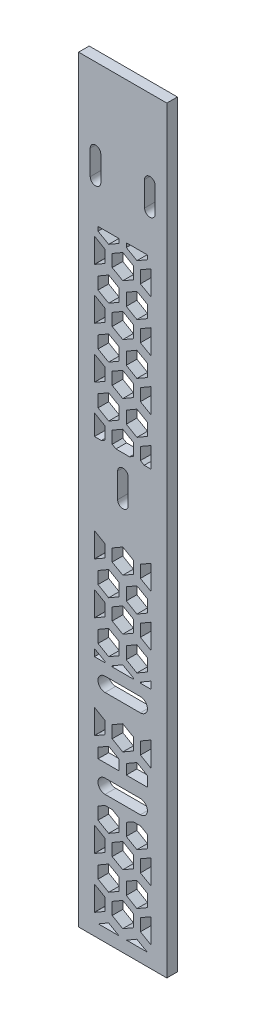
SolidWorks part; units mm, degrees
ref_plane "Front Plane" through (0, 0, 0) normal (0, 0, 1) x (1, 0, 0)
ref_plane "Top Plane" through (0, 0, 0) normal (0, 1, 0) x (1, 0, 0)
ref_plane "Right Plane" through (0, 0, 0) normal (1, 0, 0) x (0, 0, -1)
sketch "Sketch1" plane through (0, 0, 0) normal (0, 0, 1) x (1, 0, 0)
  line B0 (0, 114.5304) -> (25, 114.5304)
  line B1 (0, 114.5304) -> (0, -114.5304)
  line B2 (0, -114.5304) -> (25, -114.5304)
  line B3 (25, 114.5304) -> (25, -114.5304)
  line B4 (3.3, 89.1304) -> (0, 89.1304) construction
  line B5 (21.7, 89.1304) -> (25, 89.1304) construction
  line B6 (0, -100.1081) -> (25, -100.1081) construction
  circle B7 centre (4.8, 89.1304) radius 1.5
  circle B8 centre (20.2, 89.1304) radius 1.5
  circle B9 centre (12.5588, 13.7722) radius 1.5
  spline B10 degree 3 poles (11.075, -109.3281) (11.075, -112.3281) (14.075, -112.3281) (14.075, -109.3281) (14.075, -106.3281) (11.075, -106.3281) (11.075, -109.3281) (11.075, -112.3281) (14.075, -112.3281) knots -0.5 0 0 0 0.5 0.5 0.5 1 1 1 1.5 1.5 1.5 weights 1 0.333333 0.333333 1 0.333333 0.333333 1 0.333333 0.333333 only from (11.075, -109.3281) to (11.075, -109.3281)
sketch_block_instance "Block-sideExtraSupport-1"
sketch_block "Block-sideExtraSupport" parameters "D1"=25
extrude "Boss-Extrude1" add sketch "Sketch1" along normal blind 3 contours B1 B6 B3 B0 B9 B8 B7
sketch "Sketch2" plane through (0, 0, 3) normal (0, 0, 1) x (1, 0, 0)
  line L1 (0, -114.5304) -> (25, -114.5304) construction
  point P3 (12.5, -114.5304)
  line B0 (0, -24.3132) -> (40.525, -24.3132) construction
  line B1 (0, -24.3132) -> (0, -74.3132) construction
  line B2 (0, -74.3132) -> (40.525, -74.3132) construction
  line B3 (40.525, -24.3132) -> (40.525, -74.3132) construction
  line B4 (32.525, -24.3132) -> (28.125, -24.3132) construction
  line B5 (20.2625, -24.3132) -> (20.2625, -49.3132) construction
  line B6 (20.2625, -49.3132) -> (0, -49.3132) construction
  line B7 (20.2625, -36.8132) -> (0, -36.8132) construction
  line B8 (28.125, -64.3132) -> (32.525, -64.3132) construction
  line B9 (32.525, -64.3132) -> (32.525, -34.3132) construction
  line B10 (28.125, -64.3132) -> (28.125, -34.3132) construction
  line B11 (28.125, -34.3132) -> (32.525, -34.3132) construction
  line B12 (27.625, -64.8132) -> (33.025, -64.8132) construction
  line B13 (33.025, -64.8132) -> (33.025, -33.8132) construction
  line B14 (27.625, -33.8132) -> (33.025, -33.8132) construction
  line B15 (27.625, -64.8132) -> (27.625, -33.8132) construction
  line B16 (0, -100.1081) -> (25, -100.1081) construction
  line B17 (25, -114.5304) -> (0, -114.5304) construction
  line B18 (12.5, -100.1081) -> (12.5, -61.8132) construction
  line B19 (12.5, -114.5304) -> (12.5, -100.1081) construction
  line B20 (7.5, -36.8132) -> (17.5, -36.8132)
  line B21 (7.5, -34.8132) -> (17.5, -34.8132)
  line B22 (7.5, -38.8132) -> (17.5, -38.8132)
  line B23 (7.5, -61.8132) -> (17.5, -61.8132)
  line B24 (7.5, -63.8132) -> (17.5, -63.8132)
  line B25 (7.5, -59.8132) -> (17.5, -59.8132)
  arc B26 (7.5, -34.8132) -> (7.5, -38.8132) centre (7.5, -36.8132) ccw
  arc B27 (17.5, -38.8132) -> (17.5, -34.8132) centre (17.5, -36.8132) ccw
  arc B28 (7.5, -63.8132) -> (7.5, -59.8132) centre (7.5, -61.8132) cw
  arc B29 (17.5, -59.8132) -> (17.5, -63.8132) centre (17.5, -61.8132) cw
sketch_block_instance "Block-SidePanelSketch2-1"
sketch_block "Block-SidePanelSketch2" parameters "D1"=50, "D2"=4, "D3"=10, "D4"=8
extrude "Cut-Extrude1" cut sketch "Sketch2" against normal through all
sketch "Sketch3" plane through (0, 0, 3) normal (0, 0, 1) x (1, 0, 0)
  line L0 (12.5, 114.5304) -> (12.5, -114.5304) construction
  line L1 (0, 114.5304) -> (25, 114.5304) construction
  line L2 (0, -114.5304) -> (25, -114.5304) construction
  line L3 (4.8, 92.6304) -> (4.8, 85.6304) construction
  line L4 (6.3, 92.6304) -> (6.3, 85.6304)
  line L5 (3.3, 92.6304) -> (3.3, 85.6304)
  line L6 (20.2, 92.6304) -> (20.2, 85.6304) construction
  line L7 (18.7, 92.6304) -> (18.7, 85.6304)
  line L8 (21.7, 92.6304) -> (21.7, 85.6304)
  line L9 (12.5588, 17.2722) -> (12.5588, 10.2722) construction
  line L10 (14.0588, 17.2722) -> (14.0588, 10.2722)
  line L11 (11.0588, 17.2722) -> (11.0588, 10.2722)
  arc A1 (6.3, 92.6304) -> (3.3, 92.6304) centre (4.8, 92.6304) ccw
  arc A2 (3.3, 85.6304) -> (6.3, 85.6304) centre (4.8, 85.6304) ccw
  circle A3 centre (4.8, 89.1304) radius 1.5 construction
  arc A4 (18.7, 92.6304) -> (21.7, 92.6304) centre (20.2, 92.6304) cw
  arc A5 (21.7, 85.6304) -> (18.7, 85.6304) centre (20.2, 85.6304) cw
  arc A6 (14.0588, 17.2722) -> (11.0588, 17.2722) centre (12.5588, 17.2722) ccw
  arc A7 (11.0588, 10.2722) -> (14.0588, 10.2722) centre (12.5588, 10.2722) ccw
  circle A8 centre (12.5588, 13.7722) radius 1.5 construction
  point P6 (4.8, 89.1304)
  point P10 (12.5588, 18.7722)
  point P14 (12.5588, 13.7722)
  point P19 (4.8, 94.1304)
  point P22 (20.2, 89.1304)
  dimension "D1" = 5
  dimension "D2" = 5
extrude "Cut-Extrude2" cut sketch "Sketch3" against normal through all
sketch "Sketch4" plane through (0, 0, 3) normal (0, 0, 1) x (1, 0, 0)
  line L0 (25, 114.5304) -> (25, -114.5304) construction
  line L1 (4.5, -66.5304) -> (20.5, -66.5304)
  line L2 (4.5, -66.5304) -> (4.5, -96.5304)
  line L3 (4.5, -96.5304) -> (20.5, -96.5304)
  line L4 (20.5, -66.5304) -> (20.5, -96.5304)
  line L5 (4.5, -66.5304) -> (20.5, -96.5304) construction
  line L6 (4.5, -96.5304) -> (20.5, -66.5304) construction
  line L7 (4.5, -43.0716) -> (20.5, -43.0716)
  line L8 (4.5, -43.0716) -> (4.5, -56.0716)
  line L9 (4.5, -56.0716) -> (20.5, -56.0716)
  line L10 (20.5, -43.0716) -> (20.5, -56.0716)
  line L11 (4.5, -43.0716) -> (20.5, -56.0716) construction
  line L12 (4.5, -56.0716) -> (20.5, -43.0716) construction
  line L13 (4.5, 22.4696) -> (20.5, 22.4696)
  line L14 (4.5, 22.4696) -> (4.5, 74.5304)
  line L15 (4.5, 74.5304) -> (20.5, 74.5304)
  line L16 (20.5, 22.4696) -> (20.5, 74.5304)
  line L17 (4.5, 22.4696) -> (20.5, 74.5304) construction
  line L18 (4.5, 74.5304) -> (20.5, 22.4696) construction
  line L19 (4.5, -31.5304) -> (20.5, -31.5304)
  line L20 (4.5, -31.5304) -> (4.5, 5.4696)
  line L21 (4.5, 5.4696) -> (20.5, 5.4696)
  line L22 (20.5, -31.5304) -> (20.5, 5.4696)
  line L23 (4.5, -31.5304) -> (20.5, 5.4696) construction
  line L24 (4.5, 5.4696) -> (20.5, -31.5304) construction
  line L25 (0, 114.5304) -> (0, -114.5304) construction
  line L26 (0, -114.5304) -> (25, -114.5304) construction
  line L27 (0, 114.5304) -> (25, 114.5304) construction
  line L28 (11.5204, -100.036) -> (11.5204, -96.5719)
  line L29 (3.5204, -100.036) -> (3.5204, -96.5719)
  line L30 (3.5204, -96.5719) -> (0.5204, -94.8398)
  line L31 (0.5204, -94.8398) -> (-2.4796, -96.5719)
  line L32 (-2.4796, -96.5719) -> (-2.4796, -100.036)
  line L33 (-2.4796, -100.036) -> (0.5204, -101.7681)
  line L34 (0.5204, -101.7681) -> (3.5204, -100.036)
  line L35 (7.5204, -106.9642) -> (7.5204, -103.5001)
  line L36 (7.5204, -103.5001) -> (4.5204, -101.7681)
  line L37 (4.5204, -101.7681) -> (1.5204, -103.5001)
  line L38 (1.5204, -103.5001) -> (1.5204, -106.9642)
  line L39 (1.5204, -106.9642) -> (4.5204, -108.6963)
  line L40 (4.5204, -108.6963) -> (7.5204, -106.9642)
  line L41 (11.5204, -96.5719) -> (8.5204, -94.8398)
  line L42 (8.5204, -94.8398) -> (5.5204, -96.5719)
  line L43 (5.5204, -96.5719) -> (5.5204, -100.036)
  line L44 (5.5204, -100.036) -> (8.5204, -101.7681)
  line L45 (8.5204, -101.7681) -> (11.5204, -100.036)
  line L46 (15.5204, -106.9642) -> (15.5204, -103.5001)
  line L47 (15.5204, -103.5001) -> (12.5204, -101.7681)
  line L48 (12.5204, -101.7681) -> (9.5204, -103.5001)
  line L49 (9.5204, -103.5001) -> (9.5204, -106.9642)
  line L50 (9.5204, -106.9642) -> (12.5204, -108.6963)
  line L51 (12.5204, -108.6963) -> (15.5204, -106.9642)
  line L52 (19.5204, -100.036) -> (19.5204, -96.5719)
  line L53 (19.5204, -96.5719) -> (16.5204, -94.8398)
  line L54 (16.5204, -94.8398) -> (13.5204, -96.5719)
  line L55 (13.5204, -96.5719) -> (13.5204, -100.036)
  line L56 (13.5204, -100.036) -> (16.5204, -101.7681)
  line L57 (16.5204, -101.7681) -> (19.5204, -100.036)
  line L58 (23.5204, -106.9642) -> (23.5204, -103.5001)
  line L59 (23.5204, -103.5001) -> (20.5204, -101.7681)
  line L60 (20.5204, -101.7681) -> (17.5204, -103.5001)
  line L61 (17.5204, -103.5001) -> (17.5204, -106.9642)
  line L62 (17.5204, -106.9642) -> (20.5204, -108.6963)
  line L63 (20.5204, -108.6963) -> (23.5204, -106.9642)
  line L64 (11.5204, -85.586) -> (11.5204, -82.1219)
  line L65 (11.5204, -82.1219) -> (8.5204, -80.3898)
  line L66 (8.5204, -80.3898) -> (5.5204, -82.1219)
  line L67 (5.5204, -82.1219) -> (5.5204, -85.586)
  line L68 (5.5204, -85.586) -> (8.5204, -87.3181)
  line L69 (8.5204, -87.3181) -> (11.5204, -85.586)
  line L70 (15.5204, -92.5142) -> (15.5204, -89.0501)
  line L71 (15.5204, -89.0501) -> (12.5204, -87.3181)
  line L72 (12.5204, -87.3181) -> (9.5204, -89.0501)
  line L73 (9.5204, -89.0501) -> (9.5204, -92.5142)
  line L74 (9.5204, -92.5142) -> (12.5204, -94.2463)
  line L75 (12.5204, -94.2463) -> (15.5204, -92.5142)
  line L76 (19.5204, -85.586) -> (19.5204, -82.1219)
  line L77 (19.5204, -82.1219) -> (16.5204, -80.3898)
  line L78 (16.5204, -80.3898) -> (13.5204, -82.1219)
  line L79 (13.5204, -82.1219) -> (13.5204, -85.586)
  line L80 (13.5204, -85.586) -> (16.5204, -87.3181)
  line L81 (16.5204, -87.3181) -> (19.5204, -85.586)
  line L82 (23.5204, -92.5142) -> (23.5204, -89.0501)
  line L83 (23.5204, -89.0501) -> (20.5204, -87.3181)
  line L84 (20.5204, -87.3181) -> (17.5204, -89.0501)
  line L85 (17.5204, -89.0501) -> (17.5204, -92.5142)
  line L86 (17.5204, -92.5142) -> (20.5204, -94.2463)
  line L87 (20.5204, -94.2463) -> (23.5204, -92.5142)
  line L88 (11.5204, -71.136) -> (11.5204, -67.6719)
  line L89 (11.5204, -67.6719) -> (8.5204, -65.9398)
  line L90 (8.5204, -65.9398) -> (5.5204, -67.6719)
  line L91 (5.5204, -67.6719) -> (5.5204, -71.136)
  line L92 (5.5204, -71.136) -> (8.5204, -72.8681)
  line L93 (8.5204, -72.8681) -> (11.5204, -71.136)
  line L94 (15.5204, -78.0642) -> (15.5204, -74.6001)
  line L95 (15.5204, -74.6001) -> (12.5204, -72.8681)
  line L96 (12.5204, -72.8681) -> (9.5204, -74.6001)
  line L97 (9.5204, -74.6001) -> (9.5204, -78.0642)
  line L98 (9.5204, -78.0642) -> (12.5204, -79.7963)
  line L99 (12.5204, -79.7963) -> (15.5204, -78.0642)
  line L100 (19.5204, -71.136) -> (19.5204, -67.6719)
  line L101 (19.5204, -67.6719) -> (16.5204, -65.9398)
  line L102 (16.5204, -65.9398) -> (13.5204, -67.6719)
  line L103 (13.5204, -67.6719) -> (13.5204, -71.136)
  line L104 (13.5204, -71.136) -> (16.5204, -72.8681)
  line L105 (16.5204, -72.8681) -> (19.5204, -71.136)
  line L106 (23.5204, -78.0642) -> (23.5204, -74.6001)
  line L107 (23.5204, -74.6001) -> (20.5204, -72.8681)
  line L108 (20.5204, -72.8681) -> (17.5204, -74.6001)
  line L109 (17.5204, -74.6001) -> (17.5204, -78.0642)
  line L110 (17.5204, -78.0642) -> (20.5204, -79.7963)
  line L111 (20.5204, -79.7963) -> (23.5204, -78.0642)
  line L112 (11.5204, -56.686) -> (11.5204, -53.2219)
  line L113 (11.5204, -53.2219) -> (8.5204, -51.4898)
  line L114 (8.5204, -51.4898) -> (5.5204, -53.2219)
  line L115 (5.5204, -53.2219) -> (5.5204, -56.686)
  line L116 (5.5204, -56.686) -> (8.5204, -58.4181)
  line L117 (8.5204, -58.4181) -> (11.5204, -56.686)
  line L118 (15.5204, -63.6142) -> (15.5204, -60.1501)
  line L119 (15.5204, -60.1501) -> (12.5204, -58.4181)
  line L120 (12.5204, -58.4181) -> (9.5204, -60.1501)
  line L121 (9.5204, -60.1501) -> (9.5204, -63.6142)
  line L122 (9.5204, -63.6142) -> (12.5204, -65.3463)
  line L123 (12.5204, -65.3463) -> (15.5204, -63.6142)
  line L124 (19.5204, -56.686) -> (19.5204, -53.2219)
  line L125 (19.5204, -53.2219) -> (16.5204, -51.4898)
  line L126 (16.5204, -51.4898) -> (13.5204, -53.2219)
  line L127 (13.5204, -53.2219) -> (13.5204, -56.686)
  line L128 (13.5204, -56.686) -> (16.5204, -58.4181)
  line L129 (16.5204, -58.4181) -> (19.5204, -56.686)
  line L130 (23.5204, -63.6142) -> (23.5204, -60.1501)
  line L131 (23.5204, -60.1501) -> (20.5204, -58.4181)
  line L132 (20.5204, -58.4181) -> (17.5204, -60.1501)
  line L133 (17.5204, -60.1501) -> (17.5204, -63.6142)
  line L134 (17.5204, -63.6142) -> (20.5204, -65.3463)
  line L135 (20.5204, -65.3463) -> (23.5204, -63.6142)
  line L136 (11.5204, -42.236) -> (11.5204, -38.7719)
  line L137 (11.5204, -38.7719) -> (8.5204, -37.0398)
  line L138 (8.5204, -37.0398) -> (5.5204, -38.7719)
  line L139 (5.5204, -38.7719) -> (5.5204, -42.236)
  line L140 (5.5204, -42.236) -> (8.5204, -43.9681)
  line L141 (8.5204, -43.9681) -> (11.5204, -42.236)
  line L142 (15.5204, -49.1642) -> (15.5204, -45.7001)
  line L143 (15.5204, -45.7001) -> (12.5204, -43.9681)
  line L144 (12.5204, -43.9681) -> (9.5204, -45.7001)
  line L145 (9.5204, -45.7001) -> (9.5204, -49.1642)
  line L146 (9.5204, -49.1642) -> (12.5204, -50.8963)
  line L147 (12.5204, -50.8963) -> (15.5204, -49.1642)
  line L148 (19.5204, -42.236) -> (19.5204, -38.7719)
  line L149 (19.5204, -38.7719) -> (16.5204, -37.0398)
  line L150 (16.5204, -37.0398) -> (13.5204, -38.7719)
  line L151 (13.5204, -38.7719) -> (13.5204, -42.236)
  line L152 (13.5204, -42.236) -> (16.5204, -43.9681)
  line L153 (16.5204, -43.9681) -> (19.5204, -42.236)
  line L154 (23.5204, -49.1642) -> (23.5204, -45.7001)
  line L155 (23.5204, -45.7001) -> (20.5204, -43.9681)
  line L156 (20.5204, -43.9681) -> (17.5204, -45.7001)
  line L157 (17.5204, -45.7001) -> (17.5204, -49.1642)
  line L158 (17.5204, -49.1642) -> (20.5204, -50.8963)
  line L159 (20.5204, -50.8963) -> (23.5204, -49.1642)
  line L160 (11.5204, -27.786) -> (11.5204, -24.3219)
  line L161 (11.5204, -24.3219) -> (8.5204, -22.5898)
  line L162 (8.5204, -22.5898) -> (5.5204, -24.3219)
  line L163 (5.5204, -24.3219) -> (5.5204, -27.786)
  line L164 (5.5204, -27.786) -> (8.5204, -29.5181)
  line L165 (8.5204, -29.5181) -> (11.5204, -27.786)
  line L166 (15.5204, -34.7142) -> (15.5204, -31.2501)
  line L167 (15.5204, -31.2501) -> (12.5204, -29.5181)
  line L168 (12.5204, -29.5181) -> (9.5204, -31.2501)
  line L169 (9.5204, -31.2501) -> (9.5204, -34.7142)
  line L170 (9.5204, -34.7142) -> (12.5204, -36.4463)
  line L171 (12.5204, -36.4463) -> (15.5204, -34.7142)
  line L172 (19.5204, -27.786) -> (19.5204, -24.3219)
  line L173 (19.5204, -24.3219) -> (16.5204, -22.5898)
  line L174 (16.5204, -22.5898) -> (13.5204, -24.3219)
  line L175 (13.5204, -24.3219) -> (13.5204, -27.786)
  line L176 (13.5204, -27.786) -> (16.5204, -29.5181)
  line L177 (16.5204, -29.5181) -> (19.5204, -27.786)
  line L178 (23.5204, -34.7142) -> (23.5204, -31.2501)
  line L179 (23.5204, -31.2501) -> (20.5204, -29.5181)
  line L180 (20.5204, -29.5181) -> (17.5204, -31.2501)
  line L181 (17.5204, -31.2501) -> (17.5204, -34.7142)
  line L182 (17.5204, -34.7142) -> (20.5204, -36.4463)
  line L183 (20.5204, -36.4463) -> (23.5204, -34.7142)
  line L184 (11.5204, -13.336) -> (11.5204, -9.8719)
  line L185 (11.5204, -9.8719) -> (8.5204, -8.1398)
  line L186 (8.5204, -8.1398) -> (5.5204, -9.8719)
  line L187 (5.5204, -9.8719) -> (5.5204, -13.336)
  line L188 (5.5204, -13.336) -> (8.5204, -15.0681)
  line L189 (8.5204, -15.0681) -> (11.5204, -13.336)
  line L190 (15.5204, -20.2642) -> (15.5204, -16.8001)
  line L191 (15.5204, -16.8001) -> (12.5204, -15.0681)
  line L192 (12.5204, -15.0681) -> (9.5204, -16.8001)
  line L193 (9.5204, -16.8001) -> (9.5204, -20.2642)
  line L194 (9.5204, -20.2642) -> (12.5204, -21.9963)
  line L195 (12.5204, -21.9963) -> (15.5204, -20.2642)
  line L196 (19.5204, -13.336) -> (19.5204, -9.8719)
  line L197 (19.5204, -9.8719) -> (16.5204, -8.1398)
  line L198 (16.5204, -8.1398) -> (13.5204, -9.8719)
  line L199 (13.5204, -9.8719) -> (13.5204, -13.336)
  line L200 (13.5204, -13.336) -> (16.5204, -15.0681)
  line L201 (16.5204, -15.0681) -> (19.5204, -13.336)
  line L202 (23.5204, -20.2642) -> (23.5204, -16.8001)
  line L203 (23.5204, -16.8001) -> (20.5204, -15.0681)
  line L204 (20.5204, -15.0681) -> (17.5204, -16.8001)
  line L205 (17.5204, -16.8001) -> (17.5204, -20.2642)
  line L206 (17.5204, -20.2642) -> (20.5204, -21.9963)
  line L207 (20.5204, -21.9963) -> (23.5204, -20.2642)
  line L208 (11.5204, 1.114) -> (11.5204, 4.5781)
  line L209 (11.5204, 4.5781) -> (8.5204, 6.3102)
  line L210 (8.5204, 6.3102) -> (5.5204, 4.5781)
  line L211 (5.5204, 4.5781) -> (5.5204, 1.114)
  line L212 (5.5204, 1.114) -> (8.5204, -0.6181)
  line L213 (8.5204, -0.6181) -> (11.5204, 1.114)
  line L214 (15.5204, -5.8142) -> (15.5204, -2.3501)
  line L215 (15.5204, -2.3501) -> (12.5204, -0.6181)
  line L216 (12.5204, -0.6181) -> (9.5204, -2.3501)
  line L217 (9.5204, -2.3501) -> (9.5204, -5.8142)
  line L218 (9.5204, -5.8142) -> (12.5204, -7.5463)
  line L219 (12.5204, -7.5463) -> (15.5204, -5.8142)
  line L220 (19.5204, 1.114) -> (19.5204, 4.5781)
  line L221 (19.5204, 4.5781) -> (16.5204, 6.3102)
  line L222 (16.5204, 6.3102) -> (13.5204, 4.5781)
  line L223 (13.5204, 4.5781) -> (13.5204, 1.114)
  line L224 (13.5204, 1.114) -> (16.5204, -0.6181)
  line L225 (16.5204, -0.6181) -> (19.5204, 1.114)
  line L226 (23.5204, -5.8142) -> (23.5204, -2.3501)
  line L227 (23.5204, -2.3501) -> (20.5204, -0.6181)
  line L228 (20.5204, -0.6181) -> (17.5204, -2.3501)
  line L229 (17.5204, -2.3501) -> (17.5204, -5.8142)
  line L230 (17.5204, -5.8142) -> (20.5204, -7.5463)
  line L231 (20.5204, -7.5463) -> (23.5204, -5.8142)
  line L232 (11.5204, 15.564) -> (11.5204, 19.0281)
  line L233 (11.5204, 19.0281) -> (8.5204, 20.7602)
  line L234 (8.5204, 20.7602) -> (5.5204, 19.0281)
  line L235 (5.5204, 19.0281) -> (5.5204, 15.564)
  line L236 (5.5204, 15.564) -> (8.5204, 13.8319)
  line L237 (8.5204, 13.8319) -> (11.5204, 15.564)
  line L238 (15.5204, 8.6358) -> (15.5204, 12.0999)
  line L239 (15.5204, 12.0999) -> (12.5204, 13.8319)
  line L240 (12.5204, 13.8319) -> (9.5204, 12.0999)
  line L241 (9.5204, 12.0999) -> (9.5204, 8.6358)
  line L242 (9.5204, 8.6358) -> (12.5204, 6.9037)
  line L243 (12.5204, 6.9037) -> (15.5204, 8.6358)
  line L244 (19.5204, 15.564) -> (19.5204, 19.0281)
  line L245 (19.5204, 19.0281) -> (16.5204, 20.7602)
  line L246 (16.5204, 20.7602) -> (13.5204, 19.0281)
  line L247 (13.5204, 19.0281) -> (13.5204, 15.564)
  line L248 (13.5204, 15.564) -> (16.5204, 13.8319)
  line L249 (16.5204, 13.8319) -> (19.5204, 15.564)
  line L250 (23.5204, 8.6358) -> (23.5204, 12.0999)
  line L251 (23.5204, 12.0999) -> (20.5204, 13.8319)
  line L252 (20.5204, 13.8319) -> (17.5204, 12.0999)
  line L253 (17.5204, 12.0999) -> (17.5204, 8.6358)
  line L254 (17.5204, 8.6358) -> (20.5204, 6.9037)
  line L255 (20.5204, 6.9037) -> (23.5204, 8.6358)
  line L256 (11.5204, 30.014) -> (11.5204, 33.4781)
  line L257 (11.5204, 33.4781) -> (8.5204, 35.2102)
  line L258 (8.5204, 35.2102) -> (5.5204, 33.4781)
  line L259 (5.5204, 33.4781) -> (5.5204, 30.014)
  line L260 (5.5204, 30.014) -> (8.5204, 28.2819)
  line L261 (8.5204, 28.2819) -> (11.5204, 30.014)
  line L262 (15.5204, 23.0858) -> (15.5204, 26.5499)
  line L263 (15.5204, 26.5499) -> (12.5204, 28.2819)
  line L264 (12.5204, 28.2819) -> (9.5204, 26.5499)
  line L265 (9.5204, 26.5499) -> (9.5204, 23.0858)
  line L266 (9.5204, 23.0858) -> (12.5204, 21.3537)
  line L267 (12.5204, 21.3537) -> (15.5204, 23.0858)
  line L268 (19.5204, 30.014) -> (19.5204, 33.4781)
  line L269 (19.5204, 33.4781) -> (16.5204, 35.2102)
  line L270 (16.5204, 35.2102) -> (13.5204, 33.4781)
  line L271 (13.5204, 33.4781) -> (13.5204, 30.014)
  line L272 (13.5204, 30.014) -> (16.5204, 28.2819)
  line L273 (16.5204, 28.2819) -> (19.5204, 30.014)
  line L274 (23.5204, 23.0858) -> (23.5204, 26.5499)
  line L275 (23.5204, 26.5499) -> (20.5204, 28.2819)
  line L276 (20.5204, 28.2819) -> (17.5204, 26.5499)
  line L277 (17.5204, 26.5499) -> (17.5204, 23.0858)
  line L278 (17.5204, 23.0858) -> (20.5204, 21.3537)
  line L279 (20.5204, 21.3537) -> (23.5204, 23.0858)
  line L280 (11.5204, 44.464) -> (11.5204, 47.9281)
  line L281 (11.5204, 47.9281) -> (8.5204, 49.6602)
  line L282 (8.5204, 49.6602) -> (5.5204, 47.9281)
  line L283 (5.5204, 47.9281) -> (5.5204, 44.464)
  line L284 (5.5204, 44.464) -> (8.5204, 42.7319)
  line L285 (8.5204, 42.7319) -> (11.5204, 44.464)
  line L286 (15.5204, 37.5358) -> (15.5204, 40.9999)
  line L287 (15.5204, 40.9999) -> (12.5204, 42.7319)
  line L288 (12.5204, 42.7319) -> (9.5204, 40.9999)
  line L289 (9.5204, 40.9999) -> (9.5204, 37.5358)
  line L290 (9.5204, 37.5358) -> (12.5204, 35.8037)
  line L291 (12.5204, 35.8037) -> (15.5204, 37.5358)
  line L292 (19.5204, 44.464) -> (19.5204, 47.9281)
  line L293 (19.5204, 47.9281) -> (16.5204, 49.6602)
  line L294 (16.5204, 49.6602) -> (13.5204, 47.9281)
  line L295 (13.5204, 47.9281) -> (13.5204, 44.464)
  line L296 (13.5204, 44.464) -> (16.5204, 42.7319)
  line L297 (16.5204, 42.7319) -> (19.5204, 44.464)
  line L298 (23.5204, 37.5358) -> (23.5204, 40.9999)
  line L299 (23.5204, 40.9999) -> (20.5204, 42.7319)
  line L300 (20.5204, 42.7319) -> (17.5204, 40.9999)
  line L301 (17.5204, 40.9999) -> (17.5204, 37.5358)
  line L302 (17.5204, 37.5358) -> (20.5204, 35.8037)
  line L303 (20.5204, 35.8037) -> (23.5204, 37.5358)
  line L304 (11.5204, 58.914) -> (11.5204, 62.3781)
  line L305 (11.5204, 62.3781) -> (8.5204, 64.1102)
  line L306 (8.5204, 64.1102) -> (5.5204, 62.3781)
  line L307 (5.5204, 62.3781) -> (5.5204, 58.914)
  line L308 (5.5204, 58.914) -> (8.5204, 57.1819)
  line L309 (8.5204, 57.1819) -> (11.5204, 58.914)
  line L310 (15.5204, 51.9858) -> (15.5204, 55.4499)
  line L311 (15.5204, 55.4499) -> (12.5204, 57.1819)
  line L312 (12.5204, 57.1819) -> (9.5204, 55.4499)
  line L313 (9.5204, 55.4499) -> (9.5204, 51.9858)
  line L314 (9.5204, 51.9858) -> (12.5204, 50.2537)
  line L315 (12.5204, 50.2537) -> (15.5204, 51.9858)
  line L316 (19.5204, 58.914) -> (19.5204, 62.3781)
  line L317 (19.5204, 62.3781) -> (16.5204, 64.1102)
  line L318 (16.5204, 64.1102) -> (13.5204, 62.3781)
  line L319 (13.5204, 62.3781) -> (13.5204, 58.914)
  line L320 (13.5204, 58.914) -> (16.5204, 57.1819)
  line L321 (16.5204, 57.1819) -> (19.5204, 58.914)
  line L322 (23.5204, 51.9858) -> (23.5204, 55.4499)
  line L323 (23.5204, 55.4499) -> (20.5204, 57.1819)
  line L324 (20.5204, 57.1819) -> (17.5204, 55.4499)
  line L325 (17.5204, 55.4499) -> (17.5204, 51.9858)
  line L326 (17.5204, 51.9858) -> (20.5204, 50.2537)
  line L327 (20.5204, 50.2537) -> (23.5204, 51.9858)
  line L328 (11.5204, 73.364) -> (11.5204, 76.8281)
  line L329 (11.5204, 76.8281) -> (8.5204, 78.5602)
  line L330 (8.5204, 78.5602) -> (5.5204, 76.8281)
  line L331 (5.5204, 76.8281) -> (5.5204, 73.364)
  line L332 (5.5204, 73.364) -> (8.5204, 71.6319)
  line L333 (8.5204, 71.6319) -> (11.5204, 73.364)
  line L334 (15.5204, 66.4358) -> (15.5204, 69.8999)
  line L335 (15.5204, 69.8999) -> (12.5204, 71.6319)
  line L336 (12.5204, 71.6319) -> (9.5204, 69.8999)
  line L337 (9.5204, 69.8999) -> (9.5204, 66.4358)
  line L338 (9.5204, 66.4358) -> (12.5204, 64.7037)
  line L339 (12.5204, 64.7037) -> (15.5204, 66.4358)
  line L340 (19.5204, 73.364) -> (19.5204, 76.8281)
  line L341 (19.5204, 76.8281) -> (16.5204, 78.5602)
  line L342 (16.5204, 78.5602) -> (13.5204, 76.8281)
  line L343 (13.5204, 76.8281) -> (13.5204, 73.364)
  line L344 (13.5204, 73.364) -> (16.5204, 71.6319)
  line L345 (16.5204, 71.6319) -> (19.5204, 73.364)
  line L346 (23.5204, 66.4358) -> (23.5204, 69.8999)
  line L347 (23.5204, 69.8999) -> (20.5204, 71.6319)
  line L348 (20.5204, 71.6319) -> (17.5204, 69.8999)
  line L349 (17.5204, 69.8999) -> (17.5204, 66.4358)
  line L350 (17.5204, 66.4358) -> (20.5204, 64.7037)
  line L351 (20.5204, 64.7037) -> (23.5204, 66.4358)
  line L352 (3.5204, -85.586) -> (3.5204, -82.1219)
  line L353 (3.5204, -82.1219) -> (0.5204, -80.3898)
  line L354 (0.5204, -80.3898) -> (-2.4796, -82.1219)
  line L355 (-2.4796, -82.1219) -> (-2.4796, -85.586)
  line L356 (-2.4796, -85.586) -> (0.5204, -87.3181)
  line L357 (0.5204, -87.3181) -> (3.5204, -85.586)
  line L358 (7.5204, -92.5142) -> (7.5204, -89.0501)
  line L359 (7.5204, -89.0501) -> (4.5204, -87.3181)
  line L360 (4.5204, -87.3181) -> (1.5204, -89.0501)
  line L361 (1.5204, -89.0501) -> (1.5204, -92.5142)
  line L362 (1.5204, -92.5142) -> (4.5204, -94.2463)
  line L363 (4.5204, -94.2463) -> (7.5204, -92.5142)
  line L364 (3.5204, -71.136) -> (3.5204, -67.6719)
  line L365 (3.5204, -67.6719) -> (0.5204, -65.9398)
  line L366 (0.5204, -65.9398) -> (-2.4796, -67.6719)
  line L367 (-2.4796, -67.6719) -> (-2.4796, -71.136)
  line L368 (-2.4796, -71.136) -> (0.5204, -72.8681)
  line L369 (0.5204, -72.8681) -> (3.5204, -71.136)
  line L370 (7.5204, -78.0642) -> (7.5204, -74.6001)
  line L371 (7.5204, -74.6001) -> (4.5204, -72.8681)
  line L372 (4.5204, -72.8681) -> (1.5204, -74.6001)
  line L373 (1.5204, -74.6001) -> (1.5204, -78.0642)
  line L374 (1.5204, -78.0642) -> (4.5204, -79.7963)
  line L375 (4.5204, -79.7963) -> (7.5204, -78.0642)
  line L376 (3.5204, -56.686) -> (3.5204, -53.2219)
  line L377 (3.5204, -53.2219) -> (0.5204, -51.4898)
  line L378 (0.5204, -51.4898) -> (-2.4796, -53.2219)
  line L379 (-2.4796, -53.2219) -> (-2.4796, -56.686)
  line L380 (-2.4796, -56.686) -> (0.5204, -58.4181)
  line L381 (0.5204, -58.4181) -> (3.5204, -56.686)
  line L382 (7.5204, -63.6142) -> (7.5204, -60.1501)
  line L383 (7.5204, -60.1501) -> (4.5204, -58.4181)
  line L384 (4.5204, -58.4181) -> (1.5204, -60.1501)
  line L385 (1.5204, -60.1501) -> (1.5204, -63.6142)
  line L386 (1.5204, -63.6142) -> (4.5204, -65.3463)
  line L387 (4.5204, -65.3463) -> (7.5204, -63.6142)
  line L388 (3.5204, -42.236) -> (3.5204, -38.7719)
  line L389 (3.5204, -38.7719) -> (0.5204, -37.0398)
  line L390 (0.5204, -37.0398) -> (-2.4796, -38.7719)
  line L391 (-2.4796, -38.7719) -> (-2.4796, -42.236)
  line L392 (-2.4796, -42.236) -> (0.5204, -43.9681)
  line L393 (0.5204, -43.9681) -> (3.5204, -42.236)
  line L394 (7.5204, -49.1642) -> (7.5204, -45.7001)
  line L395 (7.5204, -45.7001) -> (4.5204, -43.9681)
  line L396 (4.5204, -43.9681) -> (1.5204, -45.7001)
  line L397 (1.5204, -45.7001) -> (1.5204, -49.1642)
  line L398 (1.5204, -49.1642) -> (4.5204, -50.8963)
  line L399 (4.5204, -50.8963) -> (7.5204, -49.1642)
  line L400 (3.5204, -27.786) -> (3.5204, -24.3219)
  line L401 (3.5204, -24.3219) -> (0.5204, -22.5898)
  line L402 (0.5204, -22.5898) -> (-2.4796, -24.3219)
  line L403 (-2.4796, -24.3219) -> (-2.4796, -27.786)
  line L404 (-2.4796, -27.786) -> (0.5204, -29.5181)
  line L405 (0.5204, -29.5181) -> (3.5204, -27.786)
  line L406 (7.5204, -34.7142) -> (7.5204, -31.2501)
  line L407 (7.5204, -31.2501) -> (4.5204, -29.5181)
  line L408 (4.5204, -29.5181) -> (1.5204, -31.2501)
  line L409 (1.5204, -31.2501) -> (1.5204, -34.7142)
  line L410 (1.5204, -34.7142) -> (4.5204, -36.4463)
  line L411 (4.5204, -36.4463) -> (7.5204, -34.7142)
  line L412 (3.5204, -13.336) -> (3.5204, -9.8719)
  line L413 (3.5204, -9.8719) -> (0.5204, -8.1398)
  line L414 (0.5204, -8.1398) -> (-2.4796, -9.8719)
  line L415 (-2.4796, -9.8719) -> (-2.4796, -13.336)
  line L416 (-2.4796, -13.336) -> (0.5204, -15.0681)
  line L417 (0.5204, -15.0681) -> (3.5204, -13.336)
  line L418 (7.5204, -20.2642) -> (7.5204, -16.8001)
  line L419 (7.5204, -16.8001) -> (4.5204, -15.0681)
  line L420 (4.5204, -15.0681) -> (1.5204, -16.8001)
  line L421 (1.5204, -16.8001) -> (1.5204, -20.2642)
  line L422 (1.5204, -20.2642) -> (4.5204, -21.9963)
  line L423 (4.5204, -21.9963) -> (7.5204, -20.2642)
  line L424 (3.5204, 1.114) -> (3.5204, 4.5781)
  line L425 (3.5204, 4.5781) -> (0.5204, 6.3102)
  line L426 (0.5204, 6.3102) -> (-2.4796, 4.5781)
  line L427 (-2.4796, 4.5781) -> (-2.4796, 1.114)
  line L428 (-2.4796, 1.114) -> (0.5204, -0.6181)
  line L429 (0.5204, -0.6181) -> (3.5204, 1.114)
  line L430 (7.5204, -5.8142) -> (7.5204, -2.3501)
  line L431 (7.5204, -2.3501) -> (4.5204, -0.6181)
  line L432 (4.5204, -0.6181) -> (1.5204, -2.3501)
  line L433 (1.5204, -2.3501) -> (1.5204, -5.8142)
  line L434 (1.5204, -5.8142) -> (4.5204, -7.5463)
  line L435 (4.5204, -7.5463) -> (7.5204, -5.8142)
  line L436 (3.5204, 15.564) -> (3.5204, 19.0281)
  line L437 (3.5204, 19.0281) -> (0.5204, 20.7602)
  line L438 (0.5204, 20.7602) -> (-2.4796, 19.0281)
  line L439 (-2.4796, 19.0281) -> (-2.4796, 15.564)
  line L440 (-2.4796, 15.564) -> (0.5204, 13.8319)
  line L441 (0.5204, 13.8319) -> (3.5204, 15.564)
  line L442 (7.5204, 8.6358) -> (7.5204, 12.0999)
  line L443 (7.5204, 12.0999) -> (4.5204, 13.8319)
  line L444 (4.5204, 13.8319) -> (1.5204, 12.0999)
  line L445 (1.5204, 12.0999) -> (1.5204, 8.6358)
  line L446 (1.5204, 8.6358) -> (4.5204, 6.9037)
  line L447 (4.5204, 6.9037) -> (7.5204, 8.6358)
  line L448 (3.5204, 30.014) -> (3.5204, 33.4781)
  line L449 (3.5204, 33.4781) -> (0.5204, 35.2102)
  line L450 (0.5204, 35.2102) -> (-2.4796, 33.4781)
  line L451 (-2.4796, 33.4781) -> (-2.4796, 30.014)
  line L452 (-2.4796, 30.014) -> (0.5204, 28.2819)
  line L453 (0.5204, 28.2819) -> (3.5204, 30.014)
  line L454 (7.5204, 23.0858) -> (7.5204, 26.5499)
  line L455 (7.5204, 26.5499) -> (4.5204, 28.2819)
  line L456 (4.5204, 28.2819) -> (1.5204, 26.5499)
  line L457 (1.5204, 26.5499) -> (1.5204, 23.0858)
  line L458 (1.5204, 23.0858) -> (4.5204, 21.3537)
  line L459 (4.5204, 21.3537) -> (7.5204, 23.0858)
  line L460 (3.5204, 44.464) -> (3.5204, 47.9281)
  line L461 (3.5204, 47.9281) -> (0.5204, 49.6602)
  line L462 (0.5204, 49.6602) -> (-2.4796, 47.9281)
  line L463 (-2.4796, 47.9281) -> (-2.4796, 44.464)
  line L464 (-2.4796, 44.464) -> (0.5204, 42.7319)
  line L465 (0.5204, 42.7319) -> (3.5204, 44.464)
  line L466 (7.5204, 37.5358) -> (7.5204, 40.9999)
  line L467 (7.5204, 40.9999) -> (4.5204, 42.7319)
  line L468 (4.5204, 42.7319) -> (1.5204, 40.9999)
  line L469 (1.5204, 40.9999) -> (1.5204, 37.5358)
  line L470 (1.5204, 37.5358) -> (4.5204, 35.8037)
  line L471 (4.5204, 35.8037) -> (7.5204, 37.5358)
  line L472 (3.5204, 58.914) -> (3.5204, 62.3781)
  line L473 (3.5204, 62.3781) -> (0.5204, 64.1102)
  line L474 (0.5204, 64.1102) -> (-2.4796, 62.3781)
  line L475 (-2.4796, 62.3781) -> (-2.4796, 58.914)
  line L476 (-2.4796, 58.914) -> (0.5204, 57.1819)
  line L477 (0.5204, 57.1819) -> (3.5204, 58.914)
  line L478 (7.5204, 51.9858) -> (7.5204, 55.4499)
  line L479 (7.5204, 55.4499) -> (4.5204, 57.1819)
  line L480 (4.5204, 57.1819) -> (1.5204, 55.4499)
  line L481 (1.5204, 55.4499) -> (1.5204, 51.9858)
  line L482 (1.5204, 51.9858) -> (4.5204, 50.2537)
  line L483 (4.5204, 50.2537) -> (7.5204, 51.9858)
  line L484 (3.5204, 73.364) -> (3.5204, 76.8281)
  line L485 (3.5204, 76.8281) -> (0.5204, 78.5602)
  line L486 (0.5204, 78.5602) -> (-2.4796, 76.8281)
  line L487 (-2.4796, 76.8281) -> (-2.4796, 73.364)
  line L488 (-2.4796, 73.364) -> (0.5204, 71.6319)
  line L489 (0.5204, 71.6319) -> (3.5204, 73.364)
  line L490 (7.5204, 66.4358) -> (7.5204, 69.8999)
  line L491 (7.5204, 69.8999) -> (4.5204, 71.6319)
  line L492 (4.5204, 71.6319) -> (1.5204, 69.8999)
  line L493 (1.5204, 69.8999) -> (1.5204, 66.4358)
  line L494 (1.5204, 66.4358) -> (4.5204, 64.7037)
  line L495 (4.5204, 64.7037) -> (7.5204, 66.4358)
  circle A0 centre (0.5204, -98.3039) radius 3 construction
  circle A1 centre (4.5204, -105.2322) radius 3 construction
  circle A2 centre (8.5204, -98.3039) radius 3 construction
  circle A3 centre (12.5204, -105.2322) radius 3 construction
  circle A4 centre (16.5204, -98.3039) radius 3 construction
  circle A5 centre (20.5204, -105.2322) radius 3 construction
  circle A6 centre (8.5204, -83.8539) radius 3 construction
  circle A7 centre (12.5204, -90.7822) radius 3 construction
  circle A8 centre (16.5204, -83.8539) radius 3 construction
  circle A9 centre (20.5204, -90.7822) radius 3 construction
  circle A10 centre (8.5204, -69.4039) radius 3 construction
  circle A11 centre (12.5204, -76.3322) radius 3 construction
  circle A12 centre (16.5204, -69.4039) radius 3 construction
  circle A13 centre (20.5204, -76.3322) radius 3 construction
  circle A14 centre (8.5204, -54.9539) radius 3 construction
  circle A15 centre (12.5204, -61.8822) radius 3 construction
  circle A16 centre (16.5204, -54.9539) radius 3 construction
  circle A17 centre (20.5204, -61.8822) radius 3 construction
  circle A18 centre (8.5204, -40.5039) radius 3 construction
  circle A19 centre (12.5204, -47.4322) radius 3 construction
  circle A20 centre (16.5204, -40.5039) radius 3 construction
  circle A21 centre (20.5204, -47.4322) radius 3 construction
  circle A22 centre (8.5204, -26.0539) radius 3 construction
  circle A23 centre (12.5204, -32.9822) radius 3 construction
  circle A24 centre (16.5204, -26.0539) radius 3 construction
  circle A25 centre (20.5204, -32.9822) radius 3 construction
  circle A26 centre (8.5204, -11.6039) radius 3 construction
  circle A27 centre (12.5204, -18.5322) radius 3 construction
  circle A28 centre (16.5204, -11.6039) radius 3 construction
  circle A29 centre (20.5204, -18.5322) radius 3 construction
  circle A30 centre (8.5204, 2.8461) radius 3 construction
  circle A31 centre (12.5204, -4.0822) radius 3 construction
  circle A32 centre (16.5204, 2.8461) radius 3 construction
  circle A33 centre (20.5204, -4.0822) radius 3 construction
  circle A34 centre (8.5204, 17.2961) radius 3 construction
  circle A35 centre (12.5204, 10.3678) radius 3 construction
  circle A36 centre (16.5204, 17.2961) radius 3 construction
  circle A37 centre (20.5204, 10.3678) radius 3 construction
  circle A38 centre (8.5204, 31.7461) radius 3 construction
  circle A39 centre (12.5204, 24.8178) radius 3 construction
  circle A40 centre (16.5204, 31.7461) radius 3 construction
  circle A41 centre (20.5204, 24.8178) radius 3 construction
  circle A42 centre (8.5204, 46.1961) radius 3 construction
  circle A43 centre (12.5204, 39.2678) radius 3 construction
  circle A44 centre (16.5204, 46.1961) radius 3 construction
  circle A45 centre (20.5204, 39.2678) radius 3 construction
  circle A46 centre (8.5204, 60.6461) radius 3 construction
  circle A47 centre (12.5204, 53.7178) radius 3 construction
  circle A48 centre (16.5204, 60.6461) radius 3 construction
  circle A49 centre (20.5204, 53.7178) radius 3 construction
  circle A50 centre (8.5204, 75.0961) radius 3 construction
  circle A51 centre (12.5204, 68.1678) radius 3 construction
  circle A52 centre (16.5204, 75.0961) radius 3 construction
  circle A53 centre (20.5204, 68.1678) radius 3 construction
  circle A54 centre (0.5204, -83.8539) radius 3 construction
  circle A55 centre (4.5204, -90.7822) radius 3 construction
  circle A56 centre (0.5204, -69.4039) radius 3 construction
  circle A57 centre (4.5204, -76.3322) radius 3 construction
  circle A58 centre (0.5204, -54.9539) radius 3 construction
  circle A59 centre (4.5204, -61.8822) radius 3 construction
  circle A60 centre (0.5204, -40.5039) radius 3 construction
  circle A61 centre (4.5204, -47.4322) radius 3 construction
  circle A62 centre (0.5204, -26.0539) radius 3 construction
  circle A63 centre (4.5204, -32.9822) radius 3 construction
  circle A64 centre (0.5204, -11.6039) radius 3 construction
  circle A65 centre (4.5204, -18.5322) radius 3 construction
  circle A66 centre (0.5204, 2.8461) radius 3 construction
  circle A67 centre (4.5204, -4.0822) radius 3 construction
  circle A68 centre (0.5204, 17.2961) radius 3 construction
  circle A69 centre (4.5204, 10.3678) radius 3 construction
  circle A70 centre (0.5204, 31.7461) radius 3 construction
  circle A71 centre (4.5204, 24.8178) radius 3 construction
  circle A72 centre (0.5204, 46.1961) radius 3 construction
  circle A73 centre (4.5204, 39.2678) radius 3 construction
  circle A74 centre (0.5204, 60.6461) radius 3 construction
  circle A75 centre (4.5204, 53.7178) radius 3 construction
  circle A76 centre (0.5204, 75.0961) radius 3 construction
  circle A77 centre (4.5204, 68.1678) radius 3 construction
  point P0 (12.5, -81.5304)
  point P5 (12.5, -49.5716)
  point P10 (12.5, 48.5)
  point P15 (12.5, -13.0304)
  dimension "D1" = 4.5
  dimension "D2" = 4.5
  dimension "D3" = 18
  dimension "D4" = 30
  dimension "D5" = 10.4587
  dimension "D6" = 35
  dimension "D7" = 37
  dimension "D8" = 17
  dimension "D9" = 40
  dimension "D10" = 13
  dimension "D11" = 6
  dimension "D12" = 6
  dimension "D13" = 2
  dimension "D14" = 1
  dimension "D15" = 3
  dimension "D16" = 13
extrude "Cut-Extrude3" cut sketch "Sketch4" against normal blind 10 contours L41 L42 L3 | L53 L54 L3 | L85 L86 L4 L84 | L74 L75 L70 L71 L72 L73 | L362 L363 L358 L359 L360 L2 | L68 L69 L64 L65 L66 L67 | L80 L81 L76 L77 L78 L79 | L109 L110 L4 L108 | L98 L99 L94 L95 L96 L97 | L374 L375 L370 L371 L372 L2 | L104 L105 L100 L101 L1 L102 L103 | L92 L93 L88 L89 L1 L90 L91 | L114 L115 L9 L112 L113 | L126 L127 L9 L124 L125 | L157 L158 L10 L156 | L146 L147 L142 L143 L144 L145 | L398 L399 L394 L395 L396 L8 | L407 L408 L20 L19 L406 | L168 L169 L19 L166 L167 | L180 L181 L19 L22 | L176 L177 L172 L173 L174 L175 | L164 L165 L160 L161 L162 L163 | L205 L206 L22 L204 | L194 L195 L190 L191 L192 L193 | L422 L423 L418 L419 L420 L20 | L188 L189 L184 L185 L186 L187 | L200 L201 L196 L197 L198 L199 | L229 L230 L22 L228 | L218 L219 L214 L215 L216 L217 | L434 L435 L430 L431 L432 L20 | L13 L459 L454 L455 L456 L14 | L13 L267 L262 L263 L264 L265 L266 | L277 L278 L13 L16 L276 | L272 L273 L268 L269 L270 L271 | L260 L261 L256 L257 L258 L259 | L301 L302 L16 L300 | L290 L291 L286 L287 L288 L289 | L470 L471 L466 L467 L468 L14 | L284 L285 L280 L281 L282 L283 | L296 L297 L292 L293 L294 L295 | L325 L326 L16 L324 | L314 L315 L310 L311 L312 L313 | L482 L483 L478 L479 L480 L14 | L308 L309 L304 L305 L306 L307 | L320 L321 L316 L317 L318 L319 | L349 L350 L16 L348 | L338 L339 L334 L335 L336 L337 | L494 L495 L490 L491 L492 L14 | L332 L333 L328 L15 L331 | L344 L345 L340 L15 L343
sketch "Sketch5" plane through (0, 0, 3) normal (0, 0, 1) x (1, 0, 0)
  line L0 (0, 114.5304) -> (0, -114.5304) construction
  line L1 (25, -114.5304) -> (0, -114.5304)
  line L2 (25, -114.5304) -> (25, -100.1096)
  line L3 (25, -100.1096) -> (0, -100.1096)
  line L4 (0, -114.5304) -> (0, -100.1096)
  line L5 (25, -114.5304) -> (0, -100.1096) construction
  line L6 (25, -100.1096) -> (0, -114.5304) construction
  line L7 (0, 114.5304) -> (25, 114.5304) construction
  point P4 (12.5, -107.32)
  dimension "D1" = 214.64
extrude "Cut-Extrude4" cut sketch "Sketch5" against normal through all
